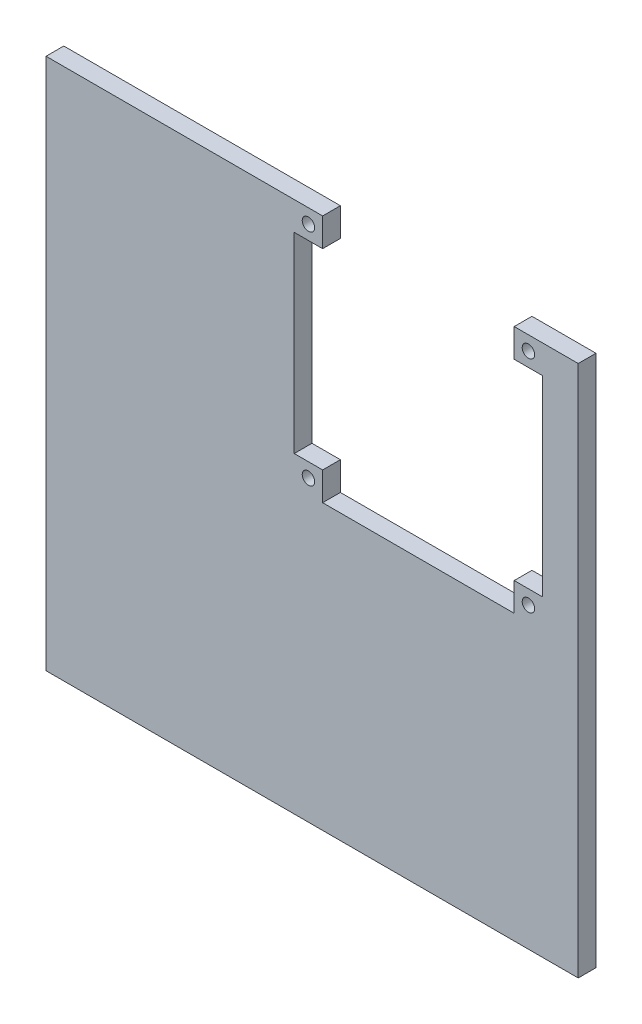
SolidWorks part; units mm, degrees
ref_plane "Front Plane" through (0, 0, 0) normal (0, 0, 1) x (1, 0, 0)
ref_plane "Top Plane" through (0, 0, 0) normal (0, 1, 0) x (1, 0, 0)
ref_plane "Right Plane" through (0, 0, 0) normal (1, 0, 0) x (0, 0, -1)
sketch "Sketch1" plane through (0, 0, 0) normal (0, 0, 1) x (1, 0, 0)
  line L1 (0, 0) -> (150, 0)
  line L2 (0, 0) -> (0, 150)
  line L3 (0, 150) -> (150, 150)
  line L4 (150, 0) -> (150, 150)
  dimension "D1" = 150
  dimension "D2" = 150
extrude "Boss-Extrude1" add sketch "Sketch1" along normal blind 5
sketch "Sketch2" plane through (0, 0, 5) normal (0, 0, 1) x (1, 0, 0)
  line L0 (77.96, 150) -> (131.96, 150)
  line L1 (131.96, 150) -> (131.96, 142)
  line L2 (131.96, 142) -> (139.96, 142)
  line L3 (139.96, 142) -> (139.96, 88)
  line L4 (139.96, 88) -> (131.96, 88)
  line L5 (131.96, 88) -> (131.96, 80)
  line L6 (131.96, 80) -> (77.96, 80)
  line L7 (77.96, 80) -> (77.96, 88)
  line L8 (77.96, 88) -> (69.96, 88)
  line L9 (69.96, 88) -> (69.96, 142)
  line L10 (69.96, 142) -> (77.96, 142)
  line L11 (77.96, 142) -> (77.96, 150)
  line L12 (77.96, 150) -> (69.96, 150) construction
  line L13 (69.96, 150) -> (69.96, 142) construction
  line L14 (69.96, 88) -> (69.96, 80) construction
  line L15 (69.96, 80) -> (77.96, 80) construction
  line L16 (131.96, 80) -> (139.96, 80) construction
  line L17 (139.96, 80) -> (139.96, 88) construction
  line L18 (139.96, 142) -> (139.96, 150) construction
  line L19 (139.96, 150) -> (131.96, 150) construction
  line L20 (73.96, 150) -> (73.96, 146) construction
  line L21 (73.96, 146) -> (69.96, 146) construction
  line L22 (73.96, 80) -> (73.96, 84) construction
  line L23 (73.96, 84) -> (69.96, 84) construction
  line L24 (150, 150) -> (0, 150) construction
  circle A0 centre (73.96, 84) radius 1.75
  circle A1 centre (73.96, 146) radius 1.75
  circle A2 centre (135.96, 146) radius 1.75
  circle A3 centre (135.96, 84) radius 1.75
  point P24 (80.8487, 121.5515)
  point P28 (141.8995, 117.3099)
  point P30 (135.96, 120.9169)
  dimension "D5" = 3.5
  dimension "D1" = 70
  dimension "D2" = 70
  dimension "D3" = 62
  dimension "D4" = 62
  dimension "D7" = 4
extrude "Cut-Extrude1" cut sketch "Sketch2" against normal through all
